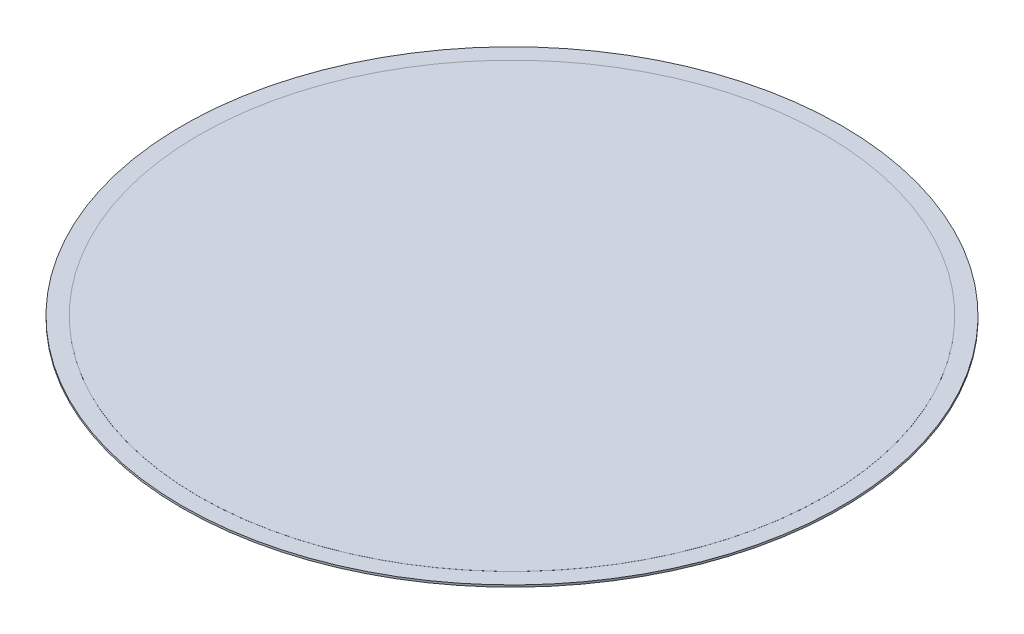
SolidWorks part; units mm, degrees
ref_plane "Front Plane" through (0, 0, 0) normal (0, 0, 1) x (1, 0, 0)
ref_plane "Top Plane" through (0, 0, 0) normal (0, 1, 0) x (1, 0, 0)
ref_plane "Right Plane" through (0, 0, 0) normal (1, 0, 0) x (0, 0, -1)
sketch "Sketch1" plane through (0, 0, 0) normal (0, 1, 0) x (1, 0, 0)
  circle A0 centre (0, 0) radius 500
  dimension "D2" = 1000
extrude "Boss-Extrude2" add sketch "Sketch1" along normal blind 3
sketch "Sketch3" plane through (0, 3, 0) normal (0, 1, 0) x (1, 0, 0)
  circle A0 centre (0, 0) radius 475
  dimension "D1" = 475
extrude "Boss-Extrude4" add sketch "Sketch3" along normal blind 0.1
